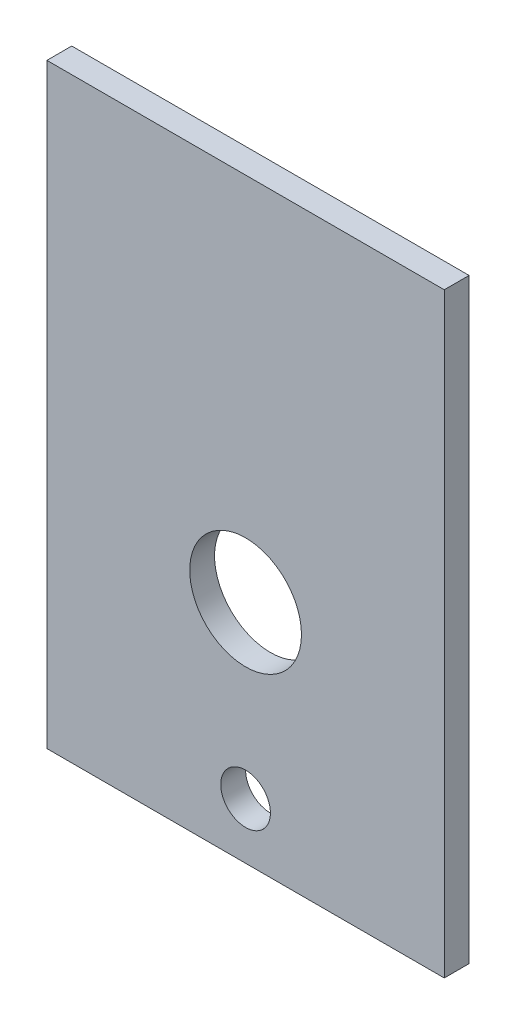
SolidWorks part; units mm, degrees
ref_plane "Front Plane" through (0, 0, 0) normal (0, 0, 1) x (1, 0, 0)
ref_plane "Top Plane" through (0, 0, 0) normal (0, 1, 0) x (1, 0, 0)
ref_plane "Right Plane" through (0, 0, 0) normal (1, 0, 0) x (0, 0, -1)
sketch "Sketch1" plane through (0, 0, 0) normal (0, 0, 1) x (1, 0, 0)
  line L0 (50.8, 14.2875) -> (50.8, 34.925) construction
  line L1 (0, 0) -> (101.6, 0)
  line L2 (0, 0) -> (0, 152.4)
  line L3 (0, 152.4) -> (101.6, 152.4)
  line L4 (101.6, 0) -> (101.6, 152.4)
  line L5 (44.45, 41.275) -> (57.15, 41.275) construction
  line L6 (44.45, 41.275) -> (44.45, 28.575) construction
  line L7 (44.45, 28.575) -> (57.15, 28.575) construction
  line L8 (57.15, 41.275) -> (57.15, 28.575) construction
  line L9 (44.45, 41.275) -> (57.15, 28.575) construction
  line L10 (44.45, 28.575) -> (57.15, 41.275) construction
  line L11 (50.8, 14.2875) -> (50.8, 0) construction
  line L12 (44.45, 38.735) -> (57.15, 38.735) construction
  line L13 (50.8, 34.925) -> (50.8, 57.785) construction
  circle A1 centre (50.8, 57.785) radius 14.2875
  circle A2 centre (50.8, 14.2875) radius 6.35
  circle A3 centre (50.8, 14.2875) radius 14.2875 construction
  circle A4 centre (50.8, 57.785) radius 19.05 construction
  point P10 (50.8, 34.925)
  point P22 (51.7714, 53.975)
  dimension "D1" = 12.7
  dimension "D4" = 28.575
  dimension "D5" = 28.575
  dimension "D7" = 38.1
  dimension "D2" = 152.4
  dimension "D3" = 101.6
  dimension "D6" = 12.7
  dimension "D8" = 2.54
  dimension "D9" = 12.7
extrude "Boss-Extrude1" add sketch "Sketch1" along normal blind 6.35
